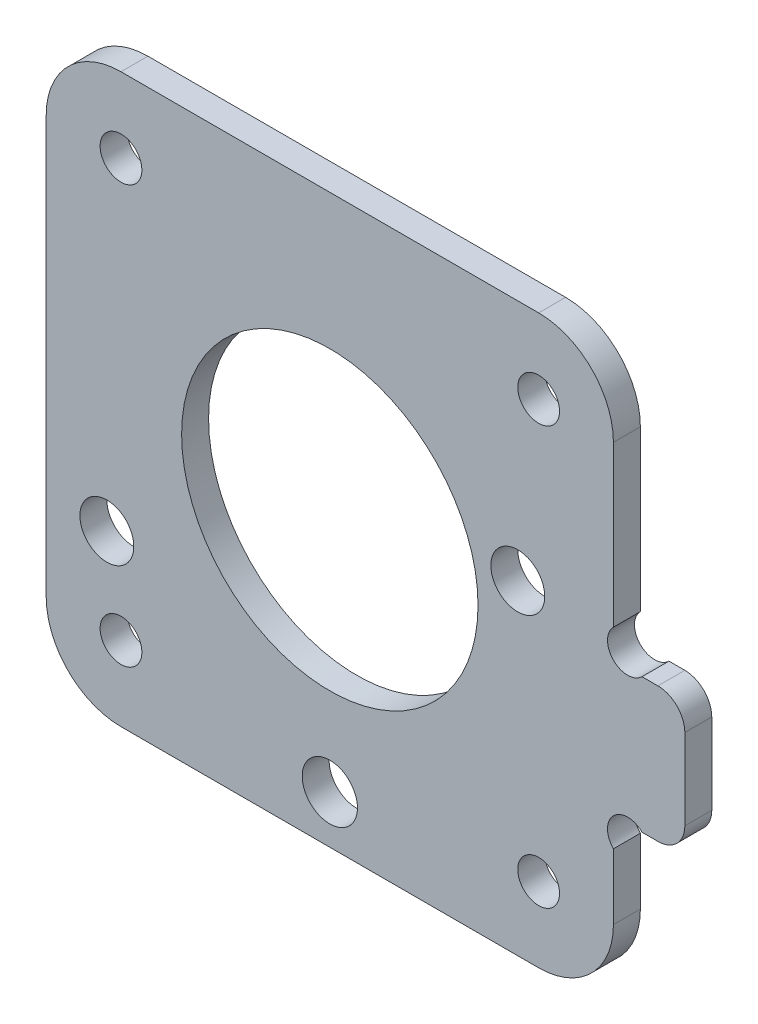
SolidWorks part; units mm, degrees
ref_plane "Front Plane" through (0, 0, 0) normal (0, 0, 1) x (1, 0, 0)
ref_plane "Top Plane" through (0, 0, 0) normal (0, 1, 0) x (1, 0, 0)
ref_plane "Right Plane" through (0, 0, 0) normal (1, 0, 0) x (0, 0, -1)
sketch "Sketch1" plane through (0, 0, 0) normal (0, 0, 1) x (1, 0, 0)
  line L0 (15.5, 15.5) -> (-15.5, -15.5) construction
  line L1 (15.5, -15.5) -> (0, 0) construction
  line L2 (0, 0) -> (0, -46.652) construction
  line L3 (-21.05, 15.5) -> (-21.05, -15.5)
  line L4 (-15.5, -21.05) -> (15.5, -21.05)
  line L5 (21.05, -15.5) -> (21.05, 15.5)
  line L6 (15.5, 21.05) -> (-15.5, 21.05)
  circle A0 centre (0, 0) radius 11
  circle A1 centre (-15.5, -15.5) radius 1.55
  circle A2 centre (15.5, 15.5) radius 1.55
  circle A3 centre (-15.5, 15.5) radius 1.55
  circle A4 centre (15.5, -15.5) radius 1.55
  arc A5 (-21.05, -15.5) -> (-15.5, -21.05) centre (-15.5, -15.5) ccw
  arc A6 (21.05, 15.5) -> (15.5, 21.05) centre (15.5, 15.5) ccw
  arc A7 (15.5, -21.05) -> (21.05, -15.5) centre (15.5, -15.5) ccw
  arc A8 (-21.05, 15.5) -> (-15.5, 21.05) centre (-15.5, 15.5) cw
  point P10 (0, 0)
  dimension "D1" = 22
  dimension "D2" = 3.1
  dimension "D3" = 31
  dimension "D4" = 4
extrude "Boss-Extrude1" add sketch "Sketch1" along normal blind 2
sketch "Sketch2" plane through (0, 0, 2) normal (0, 0, 1) x (1, 0, 0)
  line L0 (0, 0) -> (0, -46.652) construction
  circle A0 centre (0, -17.5) radius 2.05
  dimension "D2" = 4.1
  dimension "D1" = 17.5
extrude "Cut-Extrude1" cut sketch "Sketch2" against normal through all
sketch "Sketch5" plane through (0, 0, 0) normal (0, 0, -1) x (-1, 0, 0)
  line L0 (-21.05, -15.5) -> (-21.05, 15.5) construction
  line L1 (-21.05, 1.5) -> (-26.35, 1.5)
  line L2 (-21.05, 1.5) -> (-21.05, -8.5)
  line L3 (-21.05, -8.5) -> (-26.35, -8.5)
  line L4 (-26.35, 1.5) -> (-26.35, -8.5)
  line L5 (-21.05, -15.5) -> (-21.05, 15.5) construction
  line L6 (-26.35, -6.5) -> (-26.35, -0.5) construction
extrude "Boss-Extrude3" add sketch "Sketch5" against normal up to surface (2 mm away) up to face at (2.05, -17.5, 2)
fillet "Fillet1" radius 2 2 edges at (26.35, 1.5, 1) (26.35, -8.5, 1)
sketch "Sketch6" plane through (0, 0, 2) normal (0, 0, 1) x (1, 0, 0)
  line L0 (22.1107, -9.5607) -> (22.1107, -8.5) construction
  line L2 (21.05, -8.5) -> (24.35, -8.5) construction
  line L4 (22.1107, -9.5607) -> (21.05, -9.5607) construction
  line L5 (21.05, -15.5) -> (21.05, -8.5) construction
  line L6 (26.35, -3.5) -> (30.2701, -3.5) construction
  line L7 (26.35, -6.5) -> (26.35, -0.5) construction
  circle A0 centre (22.1107, 2.5607) radius 1.5
  circle A1 centre (22.1107, -9.5607) radius 1.5
  dimension "D1" = 3
extrude "Cut-Extrude3" cut sketch "Sketch6" against normal through all
sketch "Sketch7" plane through (0, 0, 0) normal (0, 0, -1) x (-1, 0, 0)
  circle A0 centre (-13.95, 3.05) radius 2 construction
  circle A1 centre (-13.95, 3.05) radius 2
  circle A2 centre (16.55, -9) radius 2 construction
  circle A3 centre (16.55, -9) radius 2
extrude "Cut-Extrude6" cut sketch "Sketch7" against normal through all contours A3
